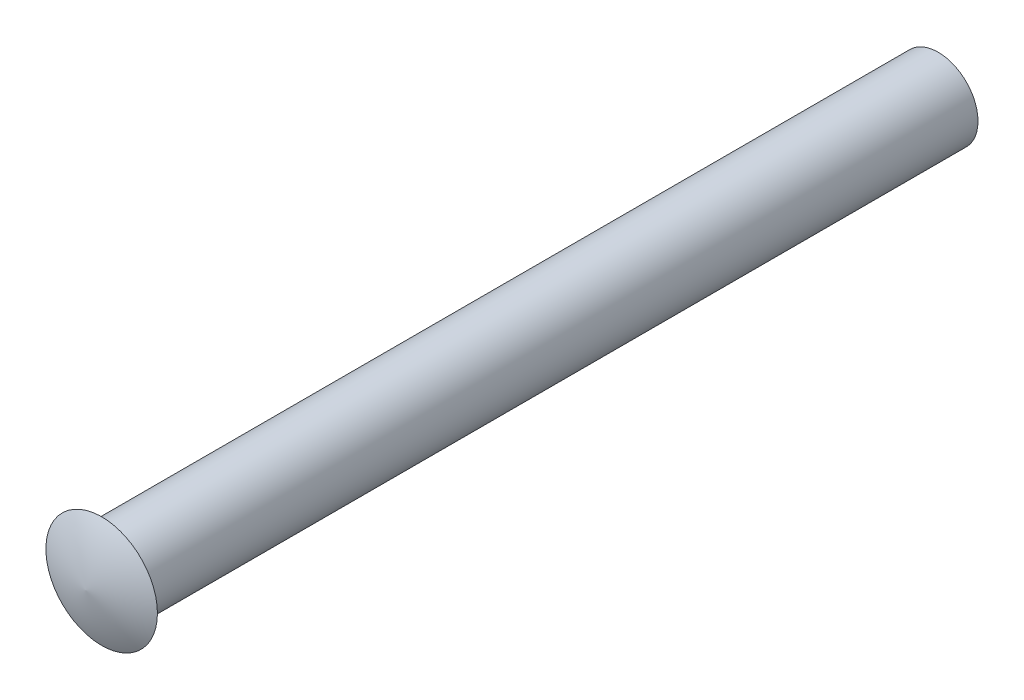
SolidWorks part; units mm, degrees
ref_plane "Front Plane" through (0, 0, 0) normal (0, 0, 1) x (1, 0, 0)
ref_plane "Top Plane" through (0, 0, 0) normal (0, 1, 0) x (1, 0, 0)
ref_plane "Right Plane" through (0, 0, 0) normal (1, 0, 0) x (0, 0, -1)
sketch "Sketch2" plane through (0, 0, 0) normal (1, 0, 0) x (0, 0, -1)
  line L0 (0, 0) -> (10.1977, 0) construction
  line L1 (0.1, 0.35) -> (0.1, 0.25)
  line L2 (0.1, 0.25) -> (5.35, 0.25)
  line L3 (5.35, 0.25) -> (5.35, 0)
  line L4 (0, 0) -> (5.35, 0)
  arc A0 (0, 0) -> (0.1, 0.35) centre (0.9955, -0.0951) cw
  dimension "D1" = 1
  dimension "D2" = 0.1
  dimension "D3" = 0.25
  dimension "D4" = 0.25
  dimension "D5" = 5.25
  dimension "D6" = 0.1
revolve "Revolve1" add sketch "Sketch2" angle 360 about L0
